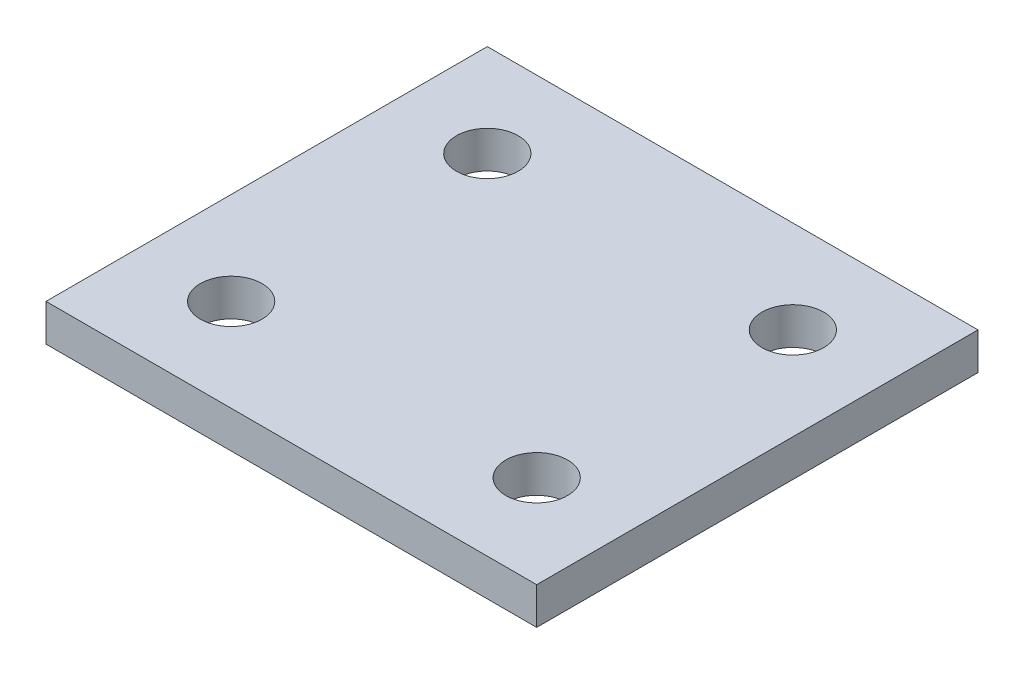
SolidWorks part; units mm, degrees
ref_plane "Plan de face" through (0, 0, 0) normal (0, 0, 1) x (1, 0, 0)
ref_plane "Plan de dessus" through (0, 0, 0) normal (0, 1, 0) x (1, 0, 0)
ref_plane "Plan de droite" through (0, 0, 0) normal (1, 0, 0) x (0, 0, -1)
sketch "Esquisse3" plane through (0, 0, 0) normal (0, 1, 0) x (1, 0, 0)
  line L0 (0, 0) -> (15.9, 0)
  line L1 (15.9, 0) -> (15.9, -14.3)
  line L2 (15.9, -14.3) -> (0, -14.3)
  line L3 (0, -14.3) -> (0, 0)
  circle A0 centre (3, -3) radius 1
  circle A1 centre (12.9, -3) radius 1
  circle A2 centre (12.9, -11.3) radius 1
  circle A3 centre (3, -11.3) radius 1
  dimension "D3" = 2
  dimension "D6" = 2
  dimension "D5" = 3
  dimension "D1" = 15.9
  dimension "D2" = 14.3
  dimension "D4" = 3
  dimension "D7" = 2
extrude "Boss.-Extru.1" add sketch "Esquisse3" along normal blind 1.2
